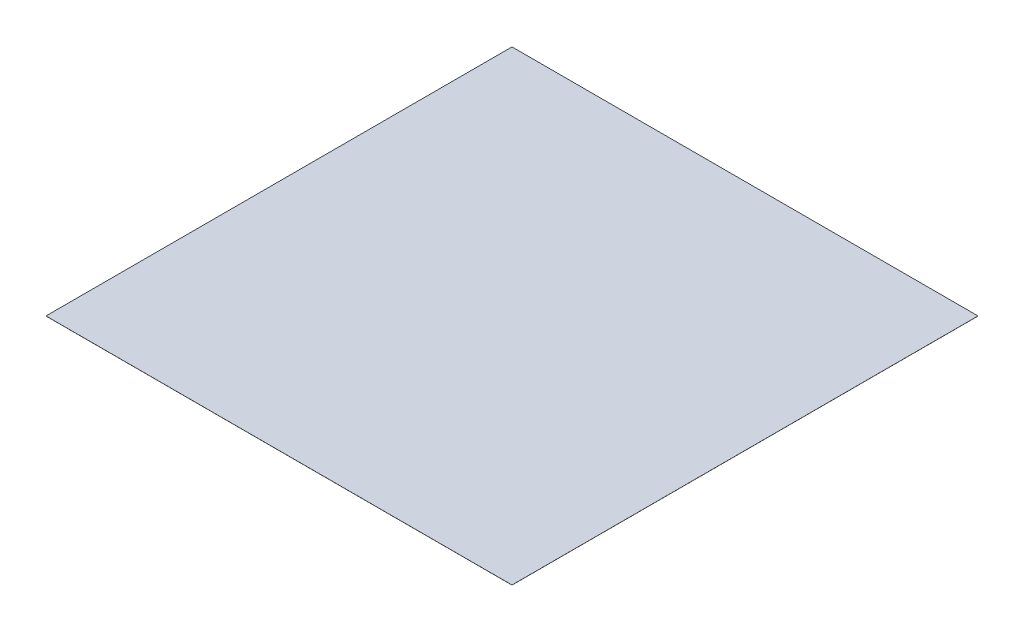
SolidWorks part; units mm, degrees
ref_plane "前视基准面" through (0, 0, 0) normal (0, 0, 1) x (1, 0, 0)
ref_plane "上视基准面" through (0, 0, 0) normal (0, 1, 0) x (1, 0, 0)
ref_plane "右视基准面" through (0, 0, 0) normal (1, 0, 0) x (0, 0, -1)
other "Configuration Table"
sketch "草图1" plane through (0, 0, 0) normal (0, 1, 0) x (1, 0, 0)
  line L1 (-500, -500) -> (500, -500)
  line L2 (-500, -500) -> (-500, 500)
  line L3 (-500, 500) -> (500, 500)
  line L4 (500, -500) -> (500, 500)
  line L5 (-500, -500) -> (500, 500) construction
  line L6 (-500, 500) -> (500, -500) construction
  point P0 (0, 0)
  dimension "D1" = 1000
extrude "凸台-拉伸1" add sketch "草图1" along normal blind 0.2
